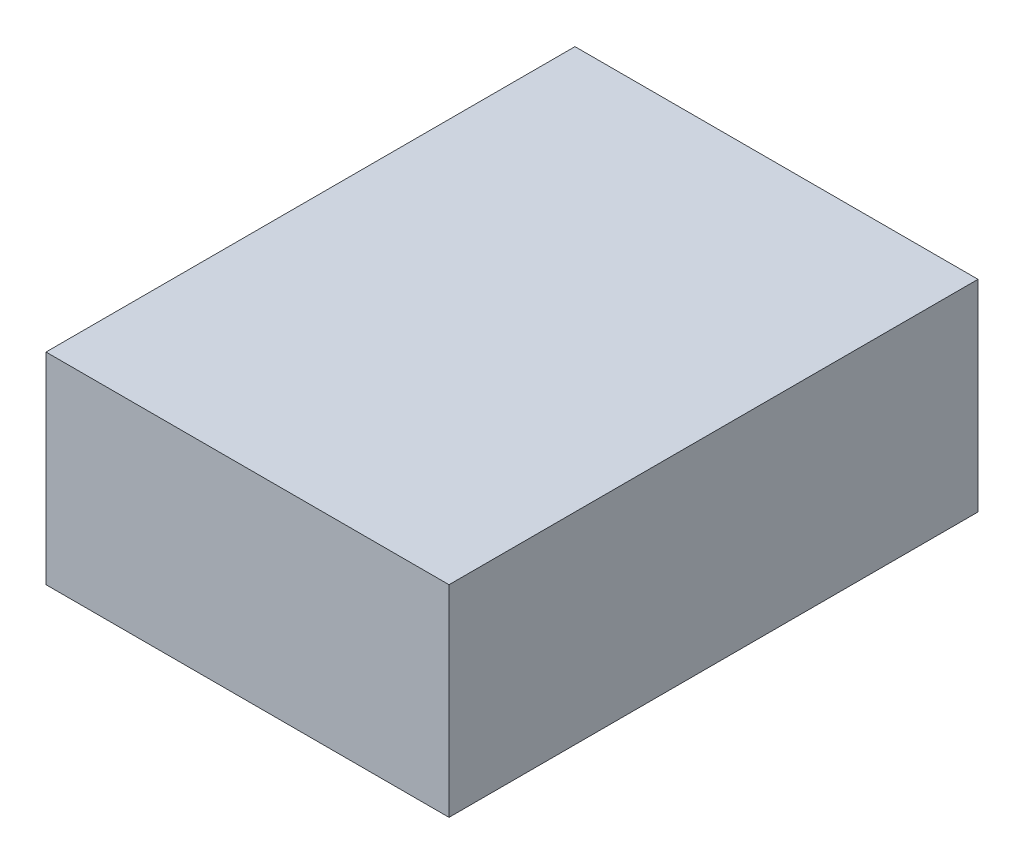
SolidWorks part; units mm, degrees
material "Pine"
ref_plane "X-Y Datum" through (0, 0, 0) normal (0, 0, 1) x (1, 0, 0)
ref_plane "X-Z Datum" through (0, 0, 0) normal (0, 1, 0) x (1, 0, 0)
ref_plane "Y-Z Datum" through (0, 0, 0) normal (1, 0, 0) x (0, 0, -1)
sketch "Sketch2" plane through (0, 0, 0) normal (0, 0, 1) x (1, 0, 0)
  line L1 (0, 0) -> (101.6, 0)
  line L2 (0, 0) -> (0, 50.8)
  line L3 (0, 50.8) -> (101.6, 50.8)
  line L4 (101.6, 0) -> (101.6, 50.8)
  dimension "D1" = 101.6
  dimension "D2" = 50.8
extrude "Boss-Extrude1" add sketch "Sketch2" along normal blind 133.35
